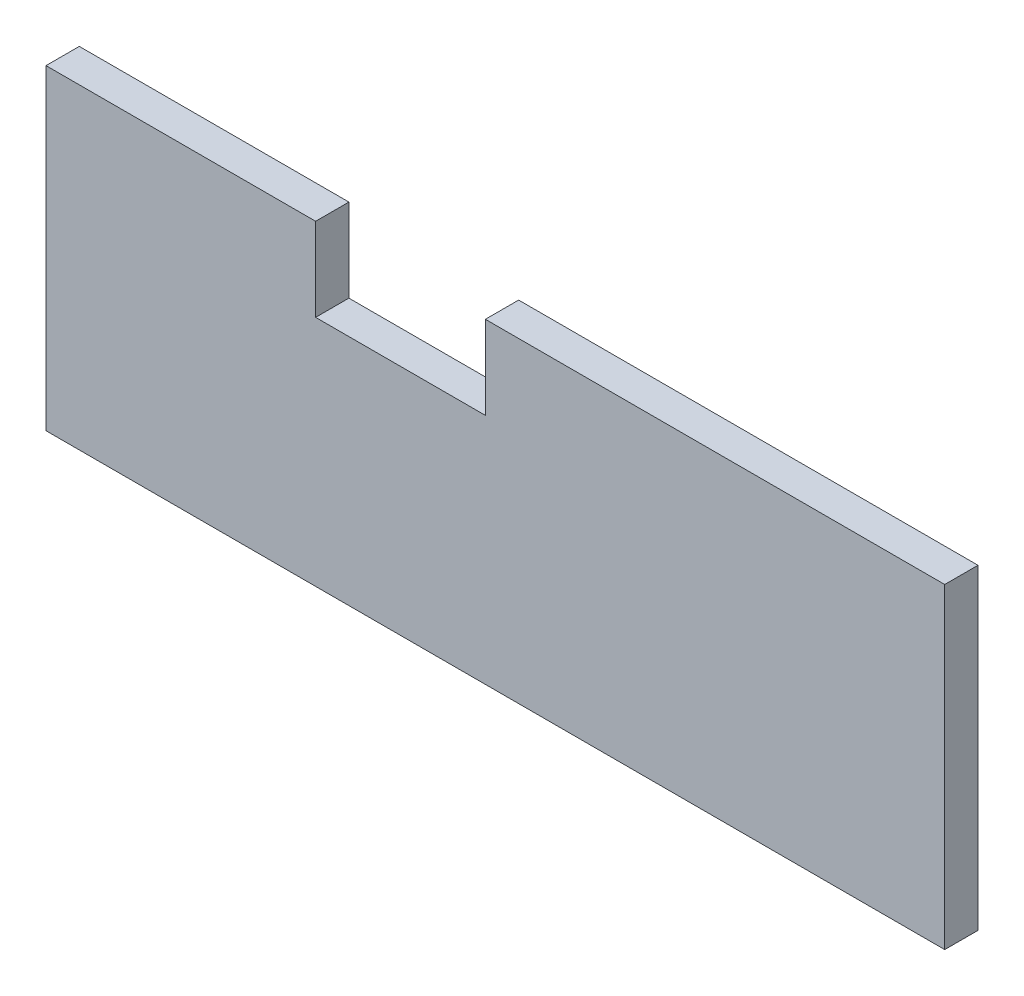
SolidWorks part; units mm, degrees
material "A516-Gr 70"
ref_plane "Front Plane" through (0, 0, 0) normal (0, 0, 1) x (1, 0, 0)
ref_plane "Top Plane" through (0, 0, 0) normal (0, 1, 0) x (1, 0, 0)
ref_plane "Right Plane" through (0, 0, 0) normal (1, 0, 0) x (0, 0, -1)
sketch "Sketch1" plane through (0, 0, 0) normal (0, 0, 1) x (1, 0, 0)
  line L1 (-135, -47.5) -> (135, -47.5)
  line L2 (-135, -47.5) -> (-135, 47.5)
  line L3 (-135, 47.5) -> (135, 47.5)
  line L4 (135, -47.5) -> (135, 47.5)
  line L5 (-135, -47.5) -> (135, 47.5) construction
  line L6 (-135, 47.5) -> (135, -47.5) construction
  point P0 (0, 0)
  dimension "D1" = 95
  dimension "D2" = 270
extrude "Boss-Extrude1" add sketch "Sketch1" along normal mid plane 10
sketch "Sketch2" plane through (0, 0, 5) normal (0, 0, 1) x (1, 0, 0)
  line L0 (135, 47.5) -> (-135, 47.5) construction
  line L1 (-54, 47.5) -> (-3, 47.5)
  line L2 (-54, 47.5) -> (-54, 22.5)
  line L3 (-54, 22.5) -> (-3, 22.5)
  line L4 (-3, 47.5) -> (-3, 22.5)
  line L5 (135, -47.5) -> (135, 47.5) construction
  dimension "D1" = 25
  dimension "D2" = 51
  dimension "D3" = 138
extrude "Cut-Extrude1" cut sketch "Sketch2" against normal blind 10
